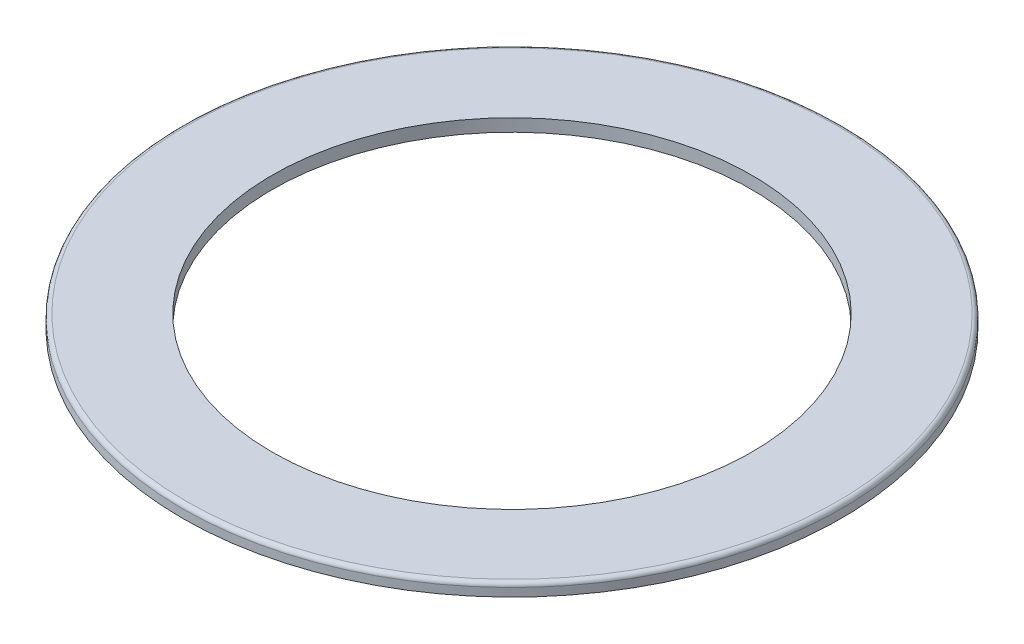
SolidWorks part; units mm, degrees
material "AISI 1010 Steel, hot rolled bar"
ref_plane "Front" through (0, 0, 0) normal (0, 0, 1) x (1, 0, 0)
ref_plane "Top" through (0, 0, 0) normal (0, 1, 0) x (1, 0, 0)
ref_plane "Right" through (0, 0, 0) normal (1, 0, 0) x (0, 0, -1)
ref_plane "Plane1" through (0, 0, 0) normal (0, 0, -1) x (-1, 0, 0)
sketch "Sketch1" plane through (0, 0, 0) normal (0, 0, -1) x (-1, 0, 0)
  line L0 (-5.75, -0.15) -> (-5.75, 0.15)
  line L1 (-5.75, 0.15) -> (-7.9, 0.15)
  line L2 (-7.9, 0.15) -> (-7.9, -0.15)
  line L3 (-7.9, -0.15) -> (-5.75, -0.15)
  line L4 (0, -0.15) -> (0, 0.15) construction
  point P6 (0, 0)
  point P8 (-5.75, 0)
  dimension "D1" = 5.75
  dimension "D2" = 2.15
  dimension "D3" = 0.3
revolve "Revolve1" add sketch "Sketch1" angle 360 about L4
fillet "Fillet1" radius 0.1 1 edges at (0, 0.15, 7.9)
